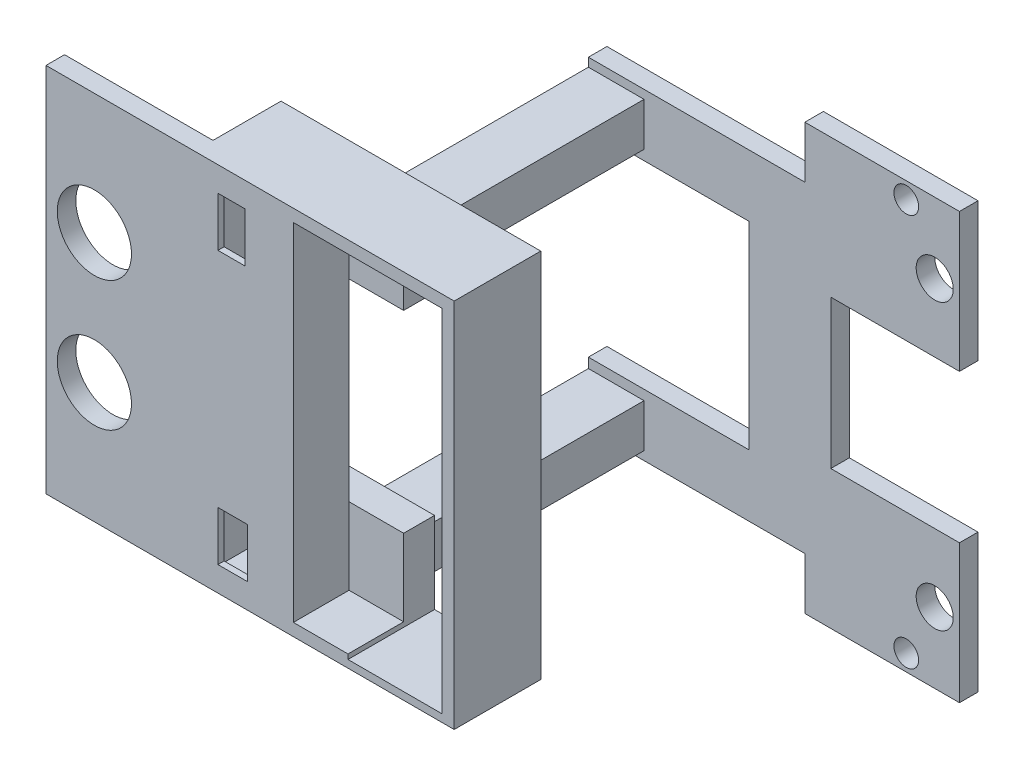
SolidWorks part; units mm, degrees
ref_plane "Front Plane" through (0, 0, 0) normal (0, 0, 1) x (1, 0, 0)
ref_plane "Top Plane" through (0, 0, 0) normal (0, 1, 0) x (1, 0, 0)
ref_plane "Right Plane" through (0, 0, 0) normal (1, 0, 0) x (0, 0, -1)
sketch "Sketch2" plane through (0, 0, 0) normal (0, 0, 1) x (1, 0, 0)
  line L0 (55, 0) -> (-55, 0) construction
  line L1 (-10.5, 15) -> (10.5, 15)
  line L2 (-10.5, 15) -> (-10.5, -15)
  line L3 (-10.5, -15) -> (10.5, -15)
  line L4 (10.5, 15) -> (10.5, -15)
  line L5 (0, -55) -> (0, 55) construction
  point P6 (-10.5, 0)
  point P7 (0, 15)
  dimension "D1" = 30
  dimension "D2" = 21
extrude "Boss-Extrude1" add sketch "Sketch2" along normal blind 7
sketch "Sketch3" plane through (0, 0, 7) normal (0, 0, 1) x (1, 0, 0)
  line L0 (-10.5, 15) -> (-10.5, -15) construction
  line L1 (-2.5, 14) -> (9.5, 14)
  line L2 (-2.5, 14) -> (-2.5, -14)
  line L3 (-2.5, -14) -> (9.5, -14)
  line L4 (9.5, 14) -> (9.5, -14)
  line L6 (10.5, -15) -> (10.5, 15) construction
  line L7 (10.5, 15) -> (-10.5, 15) construction
  line L8 (-10.5, -15) -> (10.5, -15) construction
  dimension "D1" = 8
  dimension "D2" = 1
  dimension "D3" = 1
  dimension "D4" = 1
extrude "Cut-Extrude1" cut sketch "Sketch3" against normal offset from surface (4.5 mm away) 2.5 up to face at (0, 0, 0)
sketch "Sketch4" plane through (0, 0, 0) normal (0, 0, -1) x (-1, 0, 0)
  line L0 (10.5, 15) -> (10.5, -15) construction
  line L1 (5.2688, 14) -> (9.5, 14)
  line L2 (5.2688, 14) -> (5.2688, -14)
  line L3 (5.2688, -14) -> (9.5, -14)
  line L4 (9.5, 14) -> (9.5, -14)
  line L5 (-10.5, 15) -> (10.5, 15) construction
  line L6 (10.5, -15) -> (-10.5, -15) construction
  dimension "D1" = 1
  dimension "D2" = 1
  dimension "D3" = 1
extrude "Cut-Extrude2" cut sketch "Sketch4" against normal offset from surface (6.5 mm away) 0.5 up to face at (3.5, 0, 7)
sketch "Sketch6" plane through (9.5, 0, 0) normal (-1, 0, 0) x (0, 0, 1)
  line L0 (7, 15) -> (7, -15) construction
  line L1 (7, 14) -> (6.5, 14)
  line L2 (7, 14) -> (7, 11.5)
  line L3 (7, 11.5) -> (6.5, 11.5)
  line L4 (6.5, 14) -> (6.5, 11.5)
  line L5 (2.5, 14) -> (7, 14) construction
  line L6 (7, 0) -> (0, 0.978) construction
  line L7 (7, -14) -> (7, 14) construction
  line L8 (3.8481, -11.0596) -> (3.3672, -10.9226)
  line L9 (3.1628, -13.4639) -> (3.8481, -11.0596)
  line L10 (3.1628, -13.4639) -> (2.682, -13.3268)
  line L11 (2.682, -13.3268) -> (3.3672, -10.9226)
  line L12 (0, -11.55) -> (0, 11.55) construction
  point P6 (6.75, 14)
  point P14 (7, 0)
  dimension "D1" = 0.5
  dimension "D2" = 2.5
sketch "Sketch7" plane through (0, 0, 7) normal (0, 0, 1) x (1, 0, 0)
  line L0 (-8.6, 9) -> (-6.4, 9)
  line L1 (-8.6, 13) -> (-6.4, 13)
  line L3 (-8.6, -13) -> (-6.2, -13)
  line L5 (-8.6, -9) -> (-6.2, -9)
  line L6 (-10.5, -15) -> (10.5, -15) construction
  line L7 (10.5, 15) -> (-10.5, 15) construction
  line L8 (-8.6, 13) -> (-8.6, 9)
  line L9 (-6.4, 13) -> (-6.4, 9)
  line L10 (-8.6, -9) -> (-8.6, -13)
  line L11 (-6.2, -9) -> (-6.2, -13)
  line L12 (-10.5, 15) -> (-10.5, -15) construction
  dimension "D1" = 2.2
  dimension "D2" = 4
  dimension "D3" = 2
  dimension "D4" = 2
  dimension "D5" = 4
  dimension "D6" = 2.4
  dimension "D7" = 1.9
  dimension "D8" = 1.9
sketch "Sketch8" plane through (0, 0, 0) normal (0, 0, -1) x (-1, 0, 0)
  line L0 (-10.5, 0) -> (10.5, 0) construction
  line L1 (-3, 12.3) -> (4.5, 12.3)
  line L2 (-3, 12.3) -> (-3, 8.8)
  line L3 (-3, 8.8) -> (4.5, 8.8)
  line L4 (4.5, 12.3) -> (4.5, 8.8)
  line L5 (-3, -8.8) -> (4.5, -8.8)
  line L6 (-3, -8.8) -> (-3, -12.3)
  line L7 (-3, -12.3) -> (4.5, -12.3)
  line L8 (4.5, -8.8) -> (4.5, -12.3)
  line L9 (-10.5, -15) -> (-10.5, 15) construction
  line L10 (10.5, 15) -> (10.5, -15) construction
  point P8 (-3, 10.55)
  point P9 (-3, -10.55)
  dimension "D1" = 21.1
  dimension "D2" = 7.5
  dimension "D3" = 3.5
  dimension "D4" = 7.5
extrude "Boss-Extrude3" add sketch "Sketch8" along normal blind 17.5
sketch "Sketch9" plane through (0, 0, 0) normal (0, 0, -1) x (-1, 0, 0)
  line L0 (5.2688, 14) -> (5.2688, -14) construction
  line L1 (5.2688, -14.6147) -> (-6.9263, -14.6147)
  line L2 (5.2688, -14.6147) -> (5.2688, 13.8175)
  line L3 (5.2688, 13.8175) -> (-6.9263, 13.8175)
  line L4 (-6.9263, -14.6147) -> (-6.9263, 13.8175)
sketch "Sketch10" plane through (0, 0, -17.5) normal (0, 0, -1) x (-1, 0, 0)
  line L0 (-3, 12.3) -> (-3, 8.8) construction
  line L1 (-3, 10.55) -> (4.5, 10.55) construction
  line L2 (4.5, 8.8) -> (4.5, 12.3) construction
  line L3 (3.85, 0) -> (-3.85, 0) construction
  circle A0 centre (0.9, 10.55) radius 0.95
  circle A1 centre (0.9, -10.55) radius 0.95
  dimension "D2" = 1.9
  dimension "D1" = 3.9
extrude "Cut-Extrude4" cut sketch "Sketch10" against normal blind 3
sketch "Sketch11" plane through (0, 0, -17.5) normal (0, 0, -1) x (-1, 0, 0)
  line L0 (4.5, -8.8) -> (-3, -8.8) construction
  line L1 (3.15, -8.8) -> (4.5, -8.8)
  line L2 (3.15, -8.8) -> (3.15, -12.3)
  line L3 (3.15, -12.3) -> (4.5, -12.3)
  line L4 (4.5, -8.8) -> (4.5, -12.3)
  line L5 (-3, -12.3) -> (4.5, -12.3) construction
  line L6 (-1.35, -8.8) -> (-3, -8.8)
  line L7 (-1.35, -8.8) -> (-1.35, -12.3)
  line L8 (-1.35, -12.3) -> (-3, -12.3)
  line L9 (-3, -8.8) -> (-3, -12.3)
  line L10 (-3, -8.8) -> (-3, -12.3) construction
  line L11 (3.85, 0) -> (-3.85, 0) construction
  line L12 (3.15, 12.3) -> (4.5, 12.3)
  line L13 (4.5, 8.8) -> (4.5, 12.3)
  line L14 (3.15, 8.8) -> (4.5, 8.8)
  line L15 (3.15, 8.8) -> (3.15, 12.3)
  line L16 (-1.35, 12.3) -> (-3, 12.3)
  line L17 (-1.35, 8.8) -> (-3, 8.8)
  line L18 (-3, 8.8) -> (-3, 12.3)
  line L19 (-1.35, 8.8) -> (-1.35, 12.3)
  line L20 (0.9, 10.55) -> (0.9, 14.9576) construction
  dimension "D1" = 4.5
extrude "Cut-Extrude5" cut sketch "Sketch11" against normal up to surface (17.5 mm away) up to face at (-0.75, 10.55, 0)
extrude "Cut-Extrude6" cut sketch "Sketch7" against normal blind 2
sketch "Sketch13" plane through (0, 0, 0) normal (0, 0, -1) x (-1, 0, 0)
  line L0 (5.2688, -14.6147) -> (5.2688, 13.8175) construction
  line L1 (5.2688, 7.8) -> (-9.5, 7.8)
  line L2 (5.2688, 7.8) -> (5.2688, -7.8)
  line L3 (5.2688, -7.8) -> (-9.5, -7.8)
  line L4 (-9.5, 7.8) -> (-9.5, -7.8)
  line L5 (-10.5, -15) -> (-10.5, 15) construction
  line L6 (-1.35, 8.8) -> (3.15, 8.8) construction
  line L7 (3.15, -8.8) -> (-1.35, -8.8) construction
  dimension "D1" = 1
  dimension "D2" = 1
  dimension "D3" = 1
extrude "Cut-Extrude8" cut sketch "Sketch13" against normal up to surface (2.5 mm away) up to face at (3.5, 0, 2.5)
sketch "Sketch14" plane through (0, 0, 0) normal (0, 0, -1) x (-1, 0, 0)
  line L0 (-9.5, 14) -> (-9.5, 11.5) construction
  line L1 (-9.5, 14) -> (-1.9145, 14)
  line L2 (-9.5, 14) -> (-9.5, -14.3883)
  line L3 (-9.5, -14.3883) -> (-1.9145, -14.3883)
  line L4 (-1.9145, 14) -> (-1.9145, -14.3883)
extrude "Cut-Extrude9" cut sketch "Sketch14" against normal blind 10
sketch "Sketch15" plane through (0, 0, -17.5) normal (0, 0, -1) x (-1, 0, 0)
  line L0 (3.85, 0) -> (-3.85, 0) construction
  line L1 (3.15, -17.2) -> (-26.85, -17.2)
  line L2 (3.15, -17.2) -> (3.15, 17.2)
  line L3 (3.15, 17.2) -> (-26.85, 17.2)
  line L4 (-26.85, -17.2) -> (-26.85, 17.2)
  line L5 (3.15, -8.8) -> (3.15, -12.3) construction
  point P4 (3.15, 0)
  dimension "D1" = 34.4
  dimension "D2" = 30
extrude "Boss-Extrude4" add sketch "Sketch15" along normal blind 1.5
sketch "Sketch16" plane through (0, 0, -19) normal (0, 0, -1) x (-1, 0, 0)
  line L0 (3.15, -17.2) -> (3.15, 17.2) construction
  line L1 (3.15, 8) -> (-9.85, 8)
  line L2 (3.15, 8) -> (3.15, -8)
  line L3 (3.15, -8) -> (-9.85, -8)
  line L4 (-9.85, 8) -> (-9.85, -8)
  line L5 (3.85, 0) -> (-3.85, 0) construction
  line L6 (3.15, -17.2) -> (3.15, -13)
  line L7 (3.15, 17.2) -> (-14.35, 17.2)
  line L8 (3.15, 17.2) -> (3.15, 13)
  line L9 (3.15, 13) -> (-14.35, 13)
  line L10 (-14.35, 17.2) -> (-14.35, 13)
  line L11 (3.15, -17.2) -> (-14.35, -17.2)
  line L12 (-14.35, -17.2) -> (-14.35, -13)
  line L13 (3.15, -13) -> (-14.35, -13)
  line L14 (-26.85, 17.2) -> (-26.85, -17.2) construction
  line L15 (-26.85, 6) -> (-16.45, 6)
  line L16 (-26.85, 6) -> (-26.85, -6)
  line L17 (-26.85, -6) -> (-16.45, -6)
  line L18 (-16.45, 6) -> (-16.45, -6)
  point P6 (3.15, 0)
  point P24 (-26.85, 0)
  dimension "D1" = 16
  dimension "D2" = 13
  dimension "D3" = 17.5
  dimension "D4" = 4.2
  dimension "D5" = 12
  dimension "D6" = 10.4
extrude "Cut-Extrude10" cut sketch "Sketch16" against normal blind 2
sketch "Sketch17" plane through (0, 0, -19) normal (0, 0, -1) x (-1, 0, 0)
  line L0 (-9.85, 8) -> (-9.85, -8) construction
  line L1 (3.85, 0) -> (-3.85, 0) construction
  circle A0 centre (-22.55, -15.875) radius 1
  circle A1 centre (-24.85, -11.5) radius 1.5
  circle A2 centre (-22.55, 15.875) radius 1
  circle A3 centre (-24.85, 11.5) radius 1.5
  dimension "D3" = 3
  dimension "D4" = 2
  dimension "D1" = 12.7
  dimension "D2" = 15
  dimension "D5" = 23
  dimension "D6" = 31.75
extrude "Cut-Extrude11" cut sketch "Sketch17" against normal blind 2
sketch "Sketch18" plane through (-10.5, 0, 0) normal (-1, 0, 0) x (0, 0, 1)
  line L0 (7, -15) -> (0, -15) construction
  line L1 (7, 15) -> (5.5, 15)
  line L2 (7, 15) -> (7, -15)
  line L3 (7, -15) -> (5.5, -15)
  line L4 (5.5, 15) -> (5.5, -15)
  dimension "D1" = 1.5
extrude "Boss-Extrude5" add sketch "Sketch18" along normal blind 12
sketch "Sketch19" plane through (0, 0, 5.5) normal (0, 0, -1) x (-1, 0, 0)
  line L0 (3.85, 0) -> (-3.85, 0) construction
  line L1 (21.5437, 0) -> (-29.3345, 0) construction
  line L2 (22.5, -15) -> (22.5, 0) construction
  line L3 (22.5, 15) -> (22.5, -15) construction
  line L4 (22.5, 0) -> (22.5, 15) construction
  circle A0 centre (18.589, 5.2438) radius 3
  circle A1 centre (18.589, -5.2438) radius 3
  dimension "D1" = 6
  dimension "D2" = 6
extrude "Cut-Extrude12" cut sketch "Sketch19" against normal blind 10
